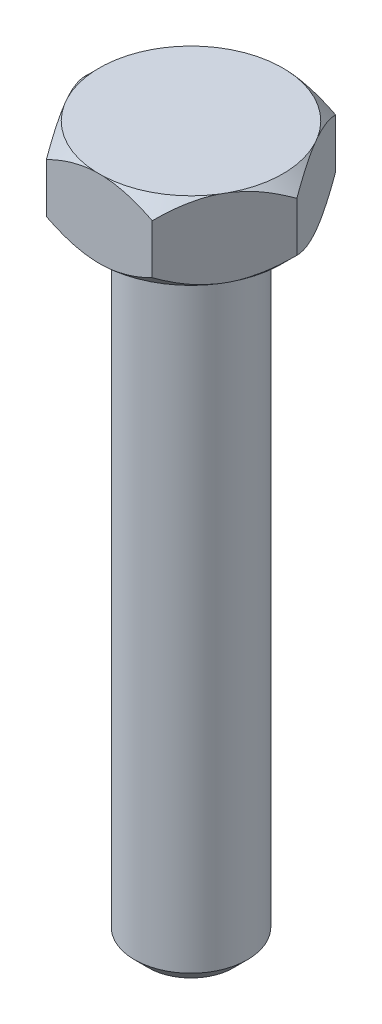
SolidWorks part; units mm, degrees
ref_plane "Спереди" through (0, 0, 0) normal (0, 0, 1) x (1, 0, 0)
ref_plane "Сверху" through (0, 0, 0) normal (0, 1, 0) x (1, 0, 0)
ref_plane "Справа" through (0, 0, 0) normal (1, 0, 0) x (0, 0, -1)
sketch "Эскиз1" plane through (0, 0, 0) normal (0, 1, 0) x (1, 0, 0)
  line L0 (-3.7528, 6.5) -> (3.7528, 6.5)
  line L1 (3.7528, 6.5) -> (7.5056, 0)
  line L2 (7.5056, 0) -> (3.7528, -6.5)
  line L3 (3.7528, -6.5) -> (-3.7528, -6.5)
  line L4 (-3.7528, -6.5) -> (-7.5056, 0)
  line L5 (-7.5056, 0) -> (-3.7528, 6.5)
  dimension "D5" = 6.5
  dimension "D2" = 120
  dimension "D3" = 120
  dimension "D4" = 120
  dimension "D6" = 6.5
  dimension "D7" = 6.5
  dimension "D8" = 6.5
  dimension "D9" = 6.5
  dimension "D10" = 120
  dimension "D11" = 6.5
extrude "Вытянуть1" add sketch "Эскиз1" against normal blind 5.5
sketch "Эскиз5" plane through (0, -5.5, 0) normal (0, -1, 0) x (1, 0, 0)
  circle A0 centre (0, 0) radius 4
  dimension "D1" = 8
extrude "Вытянуть2" add sketch "Эскиз5" along normal blind 45
chamfer "Фаска1" distance 1 angle 45 1 edges at (0, -50.5, -4)
ref_axis "Ось1" through (0, -5.5, 0) along (0, -1, 0)
ref_plane "Плоскость1" through (0, 0, 0) normal (0, 0, 1) x (1, 0, 0)
sketch "Эскиз4" plane through (0, 0, 0) normal (0, 0, 1) x (1, 0, 0)
  line L0 (-7.5056, -1) -> (-6.5056, 0)
  line L1 (-7.5056, -5.5) -> (-7.5056, 0) construction
  line L2 (-7.5056, 0) -> (-3.7528, 0) construction
  line L3 (-6.5056, 0) -> (-7.5056, 0)
  line L4 (-7.5056, 0) -> (-7.5056, -1)
  line L5 (-7.5056, -4.5) -> (-6.5056, -5.5)
  line L6 (-7.5056, -5.5) -> (-3.7528, -5.5) construction
  line L7 (-6.5056, -5.5) -> (-7.5056, -5.5)
  line L8 (-7.5056, -5.5) -> (-7.5056, -4.5)
  dimension "D1" = 1
  dimension "D2" = 1
  dimension "D3" = 1
  dimension "D4" = 1
revolve "Вырез-Повернуть1" cut sketch "Эскиз4" angle 360 about axis through (0, -5.5, 0) along (0, -1, 0)
